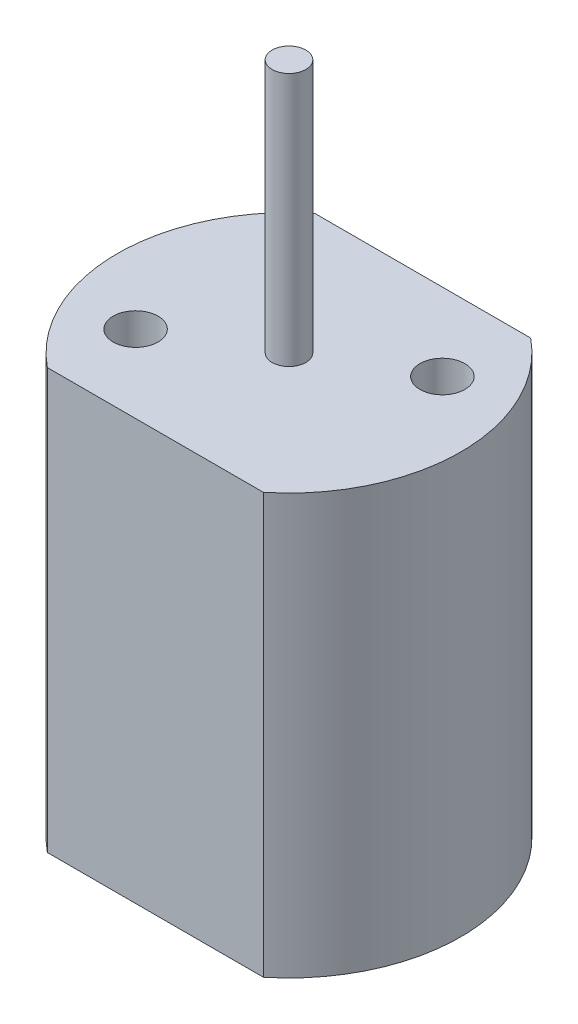
SolidWorks part; units mm, degrees
ref_plane "前视基准面" through (0, 0, 0) normal (0, 0, 1) x (1, 0, 0)
ref_plane "上视基准面" through (0, 0, 0) normal (0, 1, 0) x (1, 0, 0)
ref_plane "右视基准面" through (0, 0, 0) normal (1, 0, 0) x (0, 0, -1)
other "Configuration Table"
sketch "草图1" plane through (0, 0, 0) normal (0, 1, 0) x (1, 0, 0)
  line L1 (4.8083, 5.95) -> (-4.8083, 5.95)
  line L3 (4.8083, -5.95) -> (-4.8083, -5.95)
  arc A0 (-4.8083, 5.95) -> (-4.8083, -5.95) centre (0, 0) ccw
  circle A1 centre (0, 0) radius 5.95 construction
  arc A2 (4.8083, -5.95) -> (4.8083, 5.95) centre (0, 0) ccw
  dimension "D1" = 15.3
  dimension "D2" = 11.9
extrude "凸台-拉伸1" add sketch "草图1" along normal blind 18.7
sketch "草图2" plane through (0, 18.7, 0) normal (0, 1, 0) x (1, 0, 0)
  circle A0 centre (0, 0) radius 0.75
  dimension "D1" = 1.5
extrude "凸台-拉伸2" add sketch "草图2" along normal blind 11.3
sketch "草图3" plane through (0, 18.7, 0) normal (0, 1, 0) x (1, 0, 0)
  line L0 (0, 0) -> (3.7339, 0) construction
  line L1 (4.3301, 2.5) -> (-4.3301, -2.5) construction
  circle A0 centre (4.3301, 2.5) radius 1
  circle A1 centre (-4.3301, -2.5) radius 1
  point P5 (-5.7335, -1.0522)
  dimension "D1" = 2
  dimension "D3" = 30
  dimension "D4" = 10
  dimension "D2" = 2
extrude "切除-拉伸1" cut sketch "草图3" against normal blind 3
